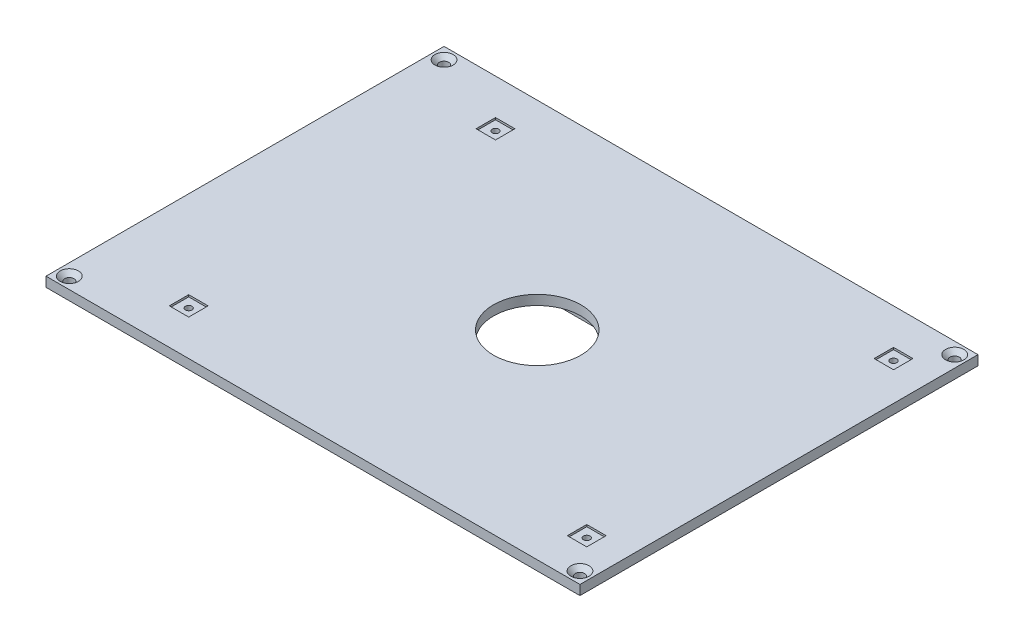
SolidWorks part; units mm, degrees
ref_plane "Plan de face" through (0, 0, 0) normal (0, 0, 1) x (1, 0, 0)
ref_plane "Plan de dessus" through (0, 0, 0) normal (0, 1, 0) x (1, 0, 0)
ref_plane "Plan de droite" through (0, 0, 0) normal (1, 0, 0) x (0, 0, -1)
sketch "Esquisse1" plane through (0, 0, 0) normal (0, 1, 0) x (1, 0, 0)
  line L1 (-137.5, -102.5) -> (137.5, -102.5)
  line L2 (-137.5, -102.5) -> (-137.5, 102.5)
  line L3 (-137.5, 102.5) -> (137.5, 102.5)
  line L4 (137.5, -102.5) -> (137.5, 102.5)
  line L5 (-137.5, -102.5) -> (137.5, 102.5) construction
  line L6 (-137.5, 102.5) -> (137.5, -102.5) construction
  point P0 (0, 0)
  dimension "D1" = 205
  dimension "D2" = 275
extrude "Boss.-Extru.1" add sketch "Esquisse1" along normal blind 5
sketch "Esquisse2" plane through (0, 5, 0) normal (0, 1, 0) x (1, 0, 0)
  line L0 (-137.5, 102.5) -> (-137.5, -102.5) construction
  line L1 (131.5, 96.5) -> (-131.5, 96.5)
  line L2 (131.5, 96.5) -> (131.5, -96.5)
  line L3 (131.5, -96.5) -> (-131.5, -96.5)
  line L4 (-131.5, 96.5) -> (-131.5, -96.5)
  line L5 (-137.5, -102.5) -> (137.5, -102.5) construction
  line L6 (137.5, 102.5) -> (-137.5, 102.5) construction
  line L7 (137.5, -102.5) -> (137.5, 102.5) construction
  dimension "D1" = 6
  dimension "D2" = 6
  dimension "D3" = 6
  dimension "D4" = 6
hole_wizard "Fraisage pour vis à tête fraisée M41" positions "Esquisse3" profile "Esquisse4" countersink size "M4" standard "Ansi Metric" end condition through all
sketch "Esquisse3" plane through (0, 5, 0) normal (0, 1, 0) x (1, 0, 0)
  point P0 (-131.5, 96.5)
  point P3 (-131.5, -96.5)
  point P6 (131.5, -96.5)
  point P9 (131.5, 96.5)
sketch "Esquisse4" plane through (-131.5, 5, -96.5) normal (1, 0, 0) x (0, 0, 1)
  line L0 (0, 0) -> (0, 5)
  line L1 (0, 5) -> (2.4, 5)
  line L2 (2.4, 5) -> (2.4, 2.3)
  line L3 (2.4, 2.3) -> (4.7, 0)
  line L5 (4.7, 0) -> (0, 0)
  line L6 (-2.4, 2.3) -> (-4.7, 0) construction
  line L11 (0, -6.35) -> (0, 107.95) construction
  dimension "Diamètre du perçage jusqu'au prochain" = 4.8
  dimension "Profondeur du perçage jusqu'au prochain" = 5
  dimension "Diamètre du fraisage entrant" = 9.4
  dimension "Angle du fraisage entrant" = 90
sketch "Esquisse5" plane through (0, 5, 0) normal (0, 1, 0) x (1, 0, 0)
  line L0 (-137.5, 0) -> (137.5, 0) construction
  line L1 (-137.5, 102.5) -> (-137.5, -102.5) construction
  line L2 (137.5, -102.5) -> (137.5, 102.5) construction
  line L4 (-92.5, 84) -> (-82.5, 84)
  line L5 (-92.5, 84) -> (-92.5, 74)
  line L6 (-92.5, 74) -> (-82.5, 74)
  line L7 (-82.5, 84) -> (-82.5, 74)
  line L8 (112.5, 84) -> (122.5, 84)
  line L9 (112.5, 84) -> (112.5, 74)
  line L10 (112.5, 74) -> (122.5, 74)
  line L11 (122.5, 84) -> (122.5, 74)
  line L12 (122.5, -84) -> (122.5, -74)
  line L13 (112.5, -74) -> (122.5, -74)
  line L14 (112.5, -84) -> (112.5, -74)
  line L15 (112.5, -84) -> (122.5, -84)
  line L16 (-82.5, -84) -> (-82.5, -74)
  line L17 (-92.5, -74) -> (-82.5, -74)
  line L18 (-92.5, -84) -> (-92.5, -74)
  line L19 (-92.5, -84) -> (-82.5, -84)
  dimension "D1" = 168
  dimension "D2" = 10
  dimension "D3" = 10
  dimension "D4" = 215
  dimension "D5" = 15
  dimension "D7" = 10
  dimension "D8" = 10
extrude "Enlèv. mat.-Extru.1" cut sketch "Esquisse5" against normal blind 1
sketch "Esquisse9" plane through (0, 5, 0) normal (0, 1, 0) x (1, 0, 0)
  line L0 (-92.5, 84) -> (-92.5, 74) construction
  line L1 (-82.5, 84) -> (-92.5, 84) construction
  circle A0 centre (13, 0) radius 22.5
  dimension "D1" = 45
  dimension "D2" = 105.5
  dimension "D3" = 84
extrude "Enlèv. mat.-Extru.2" cut sketch "Esquisse9" against normal through all both and the other way through all
hole_wizard "Dégagement M32" positions "Esquisse15" profile "Esquisse14" hole size "M3" standard "AS"
sketch "Esquisse15" plane through (0, 4, 0) normal (0, 1, 0) x (1, 0, 0)
  point P0 (-87.5, -79)
  point P2 (-87.5, 79)
  point P4 (117.5, 79)
  point P6 (117.5, -79)
sketch "Esquisse14" plane through (-87.5, 4, 79) normal (1, 0, 0) x (0, 0, 1)
  line L0 (0, 0) -> (0, 13.0215)
  line L1 (0, 13.0215) -> (1.7, 12)
  line L2 (1.7, 12) -> (1.7, 0)
  line L5 (1.7, 0) -> (0, 0)
  line L10 (0, 13.0215) -> (-1.7, 12) construction
  line L11 (0, -6.35) -> (0, 107.95) construction
  dimension "Diamètre du perçage" = 3.4
  dimension "Profondeur du perçage" = 12
  dimension "Angle de pointe" = 118
sketch "Esquisse16" plane through (0, 0, 0) normal (0, -1, 0) x (1, 0, 0)
  line L0 (-137.5, 0) -> (137.5, 0) construction
  line L1 (-65, 33) -> (35, 33)
  line L2 (-65, 33) -> (-65, 28)
  line L3 (-65, 28) -> (35, 28)
  line L4 (35, 33) -> (35, 28)
  line L5 (-137.5, -102.5) -> (-137.5, 102.5) construction
  line L6 (137.5, 102.5) -> (137.5, -102.5) construction
  line L7 (35, -33) -> (35, -28)
  line L8 (-65, -28) -> (35, -28)
  line L9 (-65, -33) -> (-65, -28)
  line L10 (-65, -33) -> (35, -33)
  circle A1 centre (13, 0) radius 22.5 construction
  dimension "D1" = 100
  dimension "D2" = 5
  dimension "D3" = 22
  dimension "D4" = 28
extrude "Boss.-Extru.2" add sketch "Esquisse16" along normal blind 7
sketch "Esquisse17" plane through (0, 0, -28) normal (0, 0, 1) x (1, 0, 0)
  line L0 (-65, -2.5) -> (35, -2.5)
  line L1 (-65, -7) -> (-65, 0) construction
  line L2 (35, -7) -> (35, 0) construction
  line L3 (35, -2.5) -> (35, 0)
  line L4 (35, 0) -> (-65, 0)
  line L5 (-65, 0) -> (-65, -2.5)
  dimension "D1" = 2.5
sketch "Esquisse18" plane through (0, 0, 28) normal (0, 0, -1) x (-1, 0, 0)
  line L0 (-35, -2.5) -> (65, -2.5)
  line L1 (-35, -7) -> (-35, 0) construction
  line L2 (65, -7) -> (65, 0) construction
  line L3 (-35, -2.5) -> (-35, 0)
  line L4 (-35, 0) -> (65, 0)
  line L5 (65, 0) -> (65, -2.5)
  dimension "D1" = 2.5
extrude "Enlèv. mat.-Extru.3" cut sketch "Esquisse18" against normal blind 1.7
extrude "Enlèv. mat.-Extru.4" cut sketch "Esquisse17" against normal blind 1.7
sketch "Esquisse19" plane through (0, 0, 0) normal (0, -1, 0) x (-1, 0, 0)
  line L5 (-35, -33) -> (65, -33) construction
  line L6 (-35, -33) -> (-40, -33)
  line L8 (-40, 33) -> (-35, 33)
  line L9 (-35, -3.7946) -> (-35.5, 0)
  line L10 (-35.5, 0) -> (-35, 3.797)
  line L11 (-35, -3.7946) -> (-35, -33)
  line L12 (-35, 3.797) -> (-35, 33)
  line L13 (-40, -33) -> (-45, -33)
  line L14 (-45, -33) -> (-45, -3.7946)
  line L16 (-45, -3.7946) -> (-40, -3.7946)
  line L17 (-40, 33) -> (-40, -3.7946)
  circle A2 centre (-13, 0) radius 22.5 construction
  point P2 (-35, -3.7946)
  dimension "D2" = 5
  dimension "D1" = 5
extrude "Boss.-Extru.4" add sketch "Esquisse19" along normal blind 7
sketch "Esquisse21" plane through (35, 0, 0) normal (-1, 0, 0) x (0, 0, 1)
  line L0 (28, -7) -> (3.7946, -7) construction
  line L1 (25.3996, -6.75) -> (4.8996, -6.75)
  line L2 (25.3996, -6.75) -> (25.3996, -0.25)
  line L3 (25.3996, -0.25) -> (4.8996, -0.25)
  line L4 (4.8996, -6.75) -> (4.8996, -0.25)
  line L5 (3.7946, -7) -> (3.7946, 0) construction
  dimension "D1" = 6.5
  dimension "D2" = 0.25
  dimension "D3" = 1.105
  dimension "D4" = 20.5
extrude "Enlèv. mat.-Extru.5" cut sketch "Esquisse21" against normal blind 13
